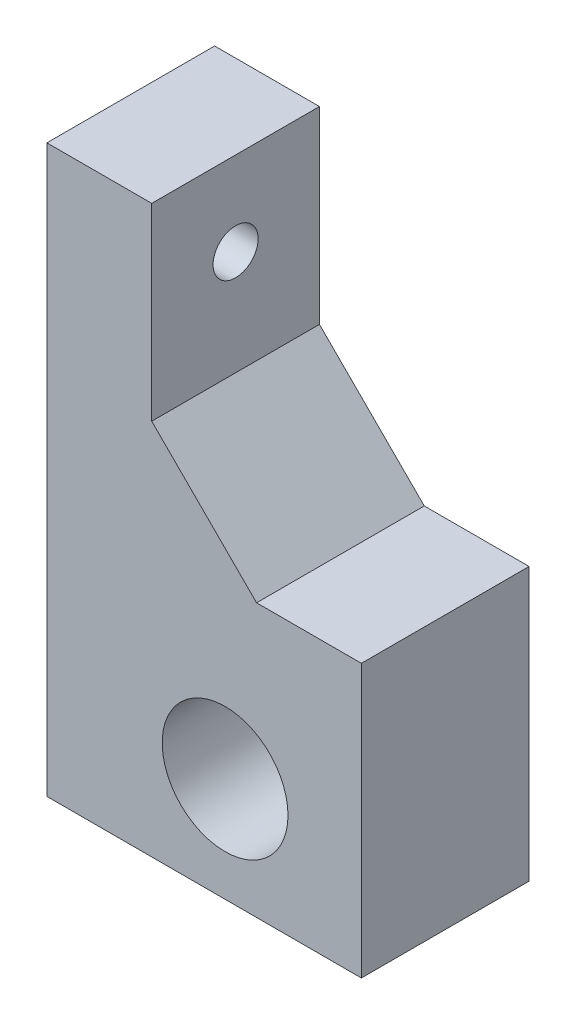
SolidWorks part; units mm, degrees
ref_plane "Front Plane" through (0, 0, 0) normal (0, 0, 1) x (1, 0, 0)
ref_plane "Top Plane" through (0, 0, 0) normal (0, 1, 0) x (1, 0, 0)
ref_plane "Right Plane" through (0, 0, 0) normal (1, 0, 0) x (0, 0, -1)
sketch "Sketch1" plane through (0, 0, 0) normal (1, 0, 0) x (0, 0, -1)
  line L1 (0, 0) -> (16, 0)
  line L2 (0, 0) -> (0, 48)
  line L3 (0, 48) -> (16, 48)
  line L4 (16, 0) -> (16, 48)
  circle A0 centre (8, 40) radius 2.15
  circle A1 centre (8, 8) radius 1.75
  dimension "D1" = 32
  dimension "D2" = 48
  dimension "D3" = 8
  dimension "D4" = 0
  dimension "D5" = 16
  dimension "D6" = 8
extrude "Boss-Extrude1" add sketch "Sketch1" along normal blind 10
sketch "Sketch2" plane through (0, 0, 0) normal (0, 0, 1) x (1, 0, 0)
  line L0 (10, 0) -> (30, 0)
  line L1 (30, 0) -> (30, 20)
  line L2 (30, 20) -> (10, 20)
  line L3 (10, 48) -> (10, 0) construction
  line L4 (10, 20) -> (10, 0)
  line L5 (10, 48) -> (0, 48) construction
  line L6 (0, 0) -> (0, -6)
  line L7 (0, -6) -> (30, -6)
  line L8 (30, -6) -> (30, 0)
  line L9 (0, 0) -> (10, 0)
  circle A0 centre (17, 3.9364) radius 6
  line M6 (0, 0) -> (10, 0)
  line M7 (10, 0) -> (10, 48)
  dimension "D1" = 7
  dimension "D2" = 20
  dimension "D3" = 20
  dimension "D4" = 44.0636
  dimension "D5" = 6
extrude "Boss-Extrude2" add sketch "Sketch2" against normal through all contours A0 L0 L1 L2 M7 | A0 L0 L6 L7 L8 M6
chamfer "Chamfer1" distance 10 angle 45 1 edges at (10, 20, -8)
